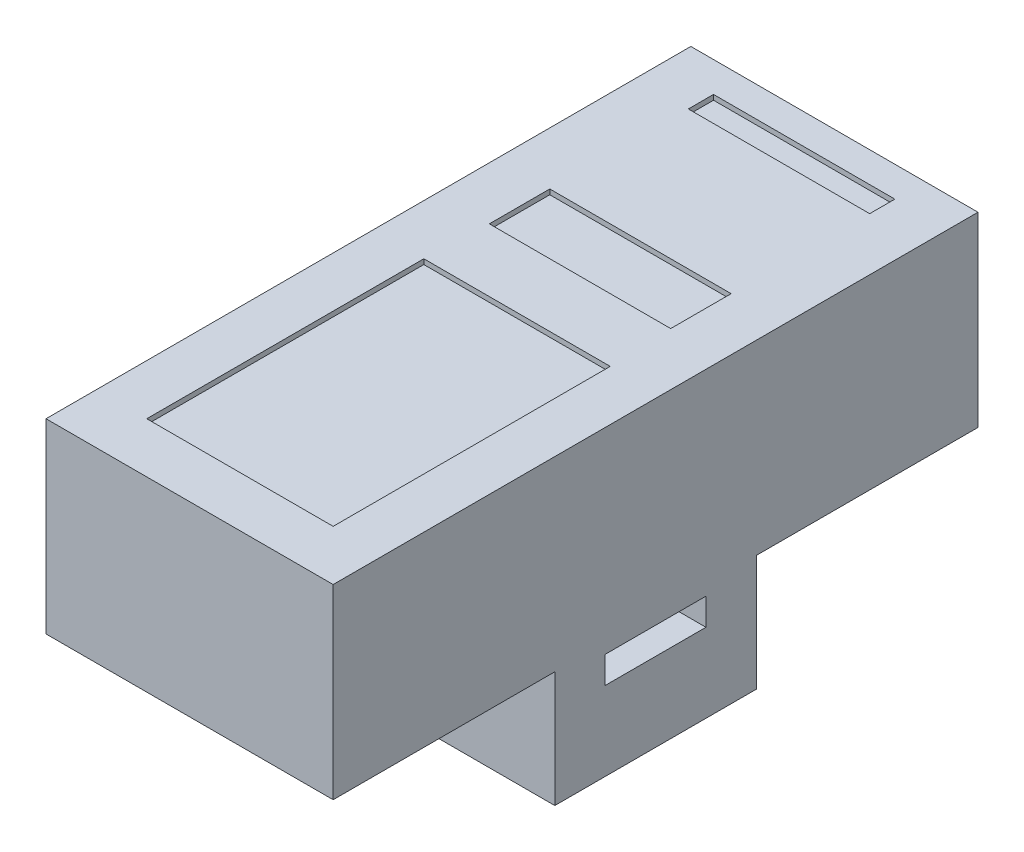
SolidWorks part; units mm, degrees
ref_plane "Спереди" through (0, 0, 0) normal (0, 0, 1) x (1, 0, 0)
ref_plane "Сверху" through (0, 0, 0) normal (0, 1, 0) x (1, 0, 0)
ref_plane "Справа" through (0, 0, 0) normal (1, 0, 0) x (0, 0, -1)
sketch "Эскиз1" plane through (0, 0, 0) normal (-1, 0, 0) x (0, 0, 1)
  line L0 (6.4, 1.25) -> (6.4, -1.25) construction
  line L1 (-6.4, 1.25) -> (6.4, 1.25)
  line L2 (-6.4, 1.25) -> (-6.4, 4.95)
  line L3 (-6.4, 4.95) -> (6.4, 4.95)
  line L4 (6.4, 1.25) -> (6.4, 4.95)
  line L5 (-2, -1.55) -> (-4.5, -1.55) construction
  dimension "D1" = 6.5
extrude "Body" add sketch "Эскиз1" against normal up to surface (5.7 mm away)
sketch "Эскиз2" plane through (0, 0, 0) normal (-1, 0, 0) x (0, 0, 1)
  line L0 (-2, 1.25) -> (-2, -1.05)
  line L1 (-2, -1.05) -> (2, -1.05)
  line L2 (2, -1.05) -> (2, 1.25)
  line L3 (2, 1.25) -> (-2, 1.25)
  line L5 (-1, 1.05) -> (1, 1.05)
  line L6 (-1, 1.05) -> (-1, 0.5149)
  line L7 (-1, 0.5149) -> (1, 0.5149)
  line L8 (1, 1.05) -> (1, 0.5149)
extrude "Teeth" add sketch "Эскиз2" against normal up to surface (5.2 mm away)
ref_plane "Plane" through (2.85, 0, 0) normal (-1, 0, 0) x (0, 0, 1)
mirror "Mirror" about plane through (2.85, 0, 0) normal (-1, 0, 0) of "Teeth"
sketch "Эскиз3" plane through (0, 4.95, 0) normal (0, 1, 0) x (1, 0, 0)
  line L0 (2.85, -6.4) -> (2.85, 6.4) construction
  line L1 (5.7, -6.4) -> (0, -6.4) construction
  line L2 (5.7, 6.4) -> (0, 6.4) construction
  line L3 (5.7, 6.4) -> (5.7, -6.4) construction
  line L4 (1, -5.4) -> (4.7, -5.4)
  line L5 (1, -5.4) -> (1, 0.1)
  line L6 (1, 0.1) -> (4.7, 0.1)
  line L7 (4.7, -5.4) -> (4.7, 0.1)
  line L8 (1, -5.4) -> (4.7, 0.1) construction
  line L9 (1, 0.1) -> (4.7, -5.4) construction
  line L11 (1.05, 2.55) -> (4.65, 2.55)
  line L12 (1.05, 2.55) -> (1.05, 1.35)
  line L13 (1.05, 1.35) -> (4.65, 1.35)
  line L14 (4.65, 2.55) -> (4.65, 1.35)
  line L15 (1.05, 2.55) -> (4.65, 1.35) construction
  line L16 (1.05, 1.35) -> (4.65, 2.55) construction
  line L17 (1.05, 5.3) -> (4.65, 5.3)
  line L18 (1.05, 5.3) -> (1.05, 5.8)
  line L19 (1.05, 5.8) -> (4.65, 5.8)
  line L20 (4.65, 5.3) -> (4.65, 5.8)
  line L21 (1.05, 5.3) -> (4.65, 5.8) construction
  line L22 (1.05, 5.8) -> (4.65, 5.3) construction
  point P6 (2.85, -2.65)
  point P13 (2.85, 1.95)
  point P19 (2.85, 5.55)
  dimension "D1" = 1
  dimension "D2" = 5.5
  dimension "D3" = 1
  dimension "D4" = 3.6
  dimension "D5" = 1.2
  dimension "D6" = 1.95
  dimension "D7" = 0.5
  dimension "D8" = 0.6
extrude "Cuts" cut sketch "Эскиз3" against normal blind 0.1
sketch "Эскиз4" plane through (0, 0, 0) normal (-1, 0, 0) x (0, 0, 1)
  text T0 " C          NO       NC\r\n" font "Arial" height 1
extrude "Text1" add sketch "Эскиз4" along normal blind 0.1
sketch "Эскиз5" plane through (0, 0, 0) normal (-1, 0, 0) x (0, 0, 1)
  text T0 "1A 125AV AC" font "Arial" height 1
extrude "Text2" add sketch "Эскиз5" along normal blind 0.1
